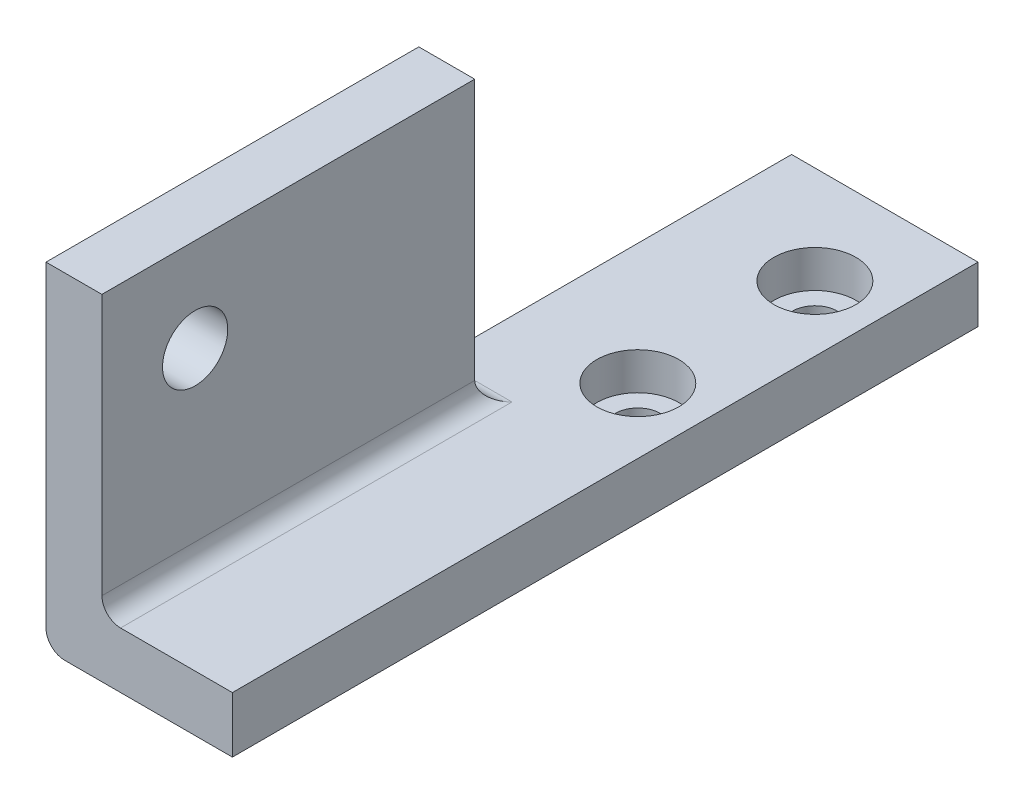
SolidWorks part; units mm, degrees
ref_plane "Front Plane" through (0, 0, 0) normal (0, 0, 1) x (1, 0, 0)
ref_plane "Top Plane" through (0, 0, 0) normal (0, 1, 0) x (1, 0, 0)
ref_plane "Right Plane" through (0, 0, 0) normal (1, 0, 0) x (0, 0, -1)
sketch "Sketch1" plane through (0, 0, 0) normal (0, 1, 0) x (1, 0, 0)
  line L0 (6.5, 5.25) -> (6.5, 14.75) construction
  line L1 (0, 0) -> (10, 0)
  line L2 (0, 0) -> (0, 20)
  line L3 (0, 20) -> (10, 20)
  line L4 (10, 0) -> (10, 20)
  circle A0 centre (6.5, 5.25) radius 1.175
  circle A1 centre (6.5, 14.75) radius 1.175
  point P9 (6.5, 10)
  point P10 (10, 10)
  dimension "D3" = 9.5
  dimension "D4" = 2.35
  dimension "D5" = 2.35
  dimension "D6" = 6.5
  dimension "D1" = 20
  dimension "D2" = 10
extrude "Boss-Extrude1" add sketch "Sketch1" along normal blind 3
sketch "Sketch2" plane through (0, 3, 0) normal (0, 1, 0) x (1, 0, 0)
  point P0 (6.5, 14.75)
  point P1 (6.5, 5.25)
hole_wizard "CBORE for M2 SHCS1" positions "Sketch2" profile "Sketch3" counterbore size "M2" standard "ANSI Metric" end condition through all
sketch "Sketch3" plane through (6.5, 3, -14.75) normal (1, 0, 0) x (0, 0, 1)
  line L0 (0, 0) -> (0, 3)
  line L1 (0, 3) -> (1.2, 3)
  line L3 (1.2, 3) -> (1.2, 2)
  line L4 (1.2, 2) -> (2.2, 2)
  line L5 (2.2, 2) -> (2.2, 0)
  line L7 (2.2, 0) -> (0, 0)
  line L11 (0, -6.35) -> (0, 107.95) construction
  dimension "Thru Hole Dia." = 2.4
  dimension "Thru Hole Depth" = 3
  dimension "C'Bore Dia." = 4.4
  dimension "C'Bore Depth" = 2
sketch "Sketch6" plane through (0, 0, 0) normal (0, 0, -1) x (-1, 0, 0)
  line L1 (0, 0) -> (-10, 0)
  line L2 (0, 0) -> (0, 3)
  line L3 (0, 3) -> (-10, 3)
  line L4 (-10, 0) -> (-10, 3)
  line L5 (-10, 3) -> (0, 3) construction
  line L6 (-10, 3) -> (-10, 0) construction
  dimension "D1" = 0
extrude "Boss-Extrude2" add sketch "Sketch6" against normal blind 20
sketch "Sketch8" plane through (0, 3, 0) normal (0, 1, 0) x (1, 0, 0)
  line L2 (0, -20) -> (3, -20)
  line L3 (0, -20) -> (0, 0)
  line L4 (0, 0) -> (3, 0)
  line L5 (3, -20) -> (3, 0)
  dimension "D1" = 3
  dimension "D2" = 20
extrude "Boss-Extrude3" add sketch "Sketch8" along normal blind 15
sketch "Sketch9" plane through (3, 0, 0) normal (1, 0, 0) x (0, 0, -1)
  line L1 (20, 3) -> (-20, 3) construction
  line L2 (-20, 18) -> (-20, 3) construction
  circle A0 centre (-15, 13) radius 1.75
  dimension "D1" = 10
  dimension "D2" = 5
  dimension "D3" = 3.5
extrude "Cut-Extrude1" cut sketch "Sketch9" against normal through all
fillet "Fillet1" radius 1 2 edges at (1.5, 3, 0) (3, 3, 10)
fillet "Fillet2" radius 1 1 edges at (0, 0, 0)
